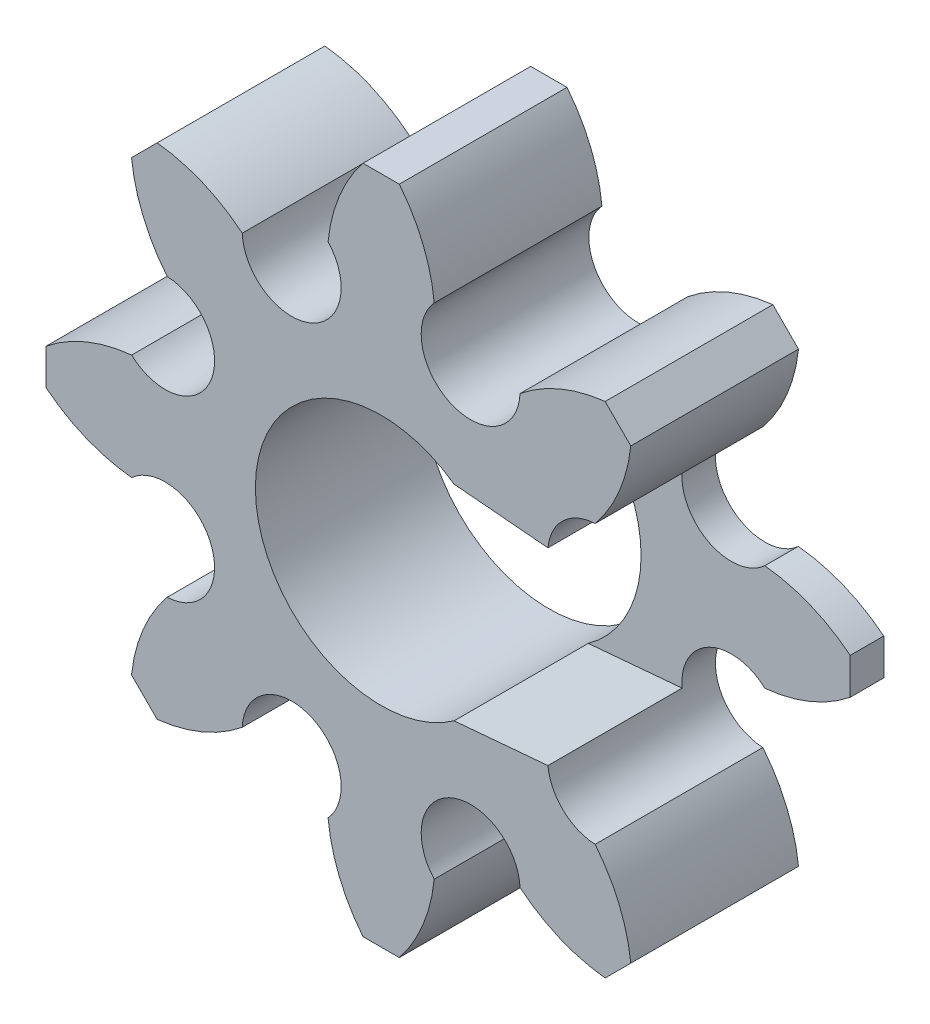
SolidWorks part; units mm, degrees
material "PLA"
ref_plane "Front Plane" through (0, 0, 0) normal (0, 0, 1) x (1, 0, 0)
ref_plane "Top Plane" through (0, 0, 0) normal (0, 1, 0) x (1, 0, 0)
ref_plane "Right Plane" through (0, 0, 0) normal (1, 0, 0) x (0, 0, -1)
other "Graphic1"
other "Graphic (Closed) -1"
sketch "Sketch1" plane through (0, 0, 0) normal (0, 0, 1) x (1, 0, 0)
  line L0 (9.559, 20.0854) -> (10.641, 20.0854)
  line L1 (16.7782, 17.5433) -> (17.5433, 16.7782)
  line L2 (20.0854, 10.641) -> (20.0854, 9.559)
  line L3 (17.5433, 3.4218) -> (16.7782, 2.6567)
  line L4 (10.641, 0.1146) -> (9.559, 0.1146)
  line L5 (3.4218, 2.6567) -> (2.6567, 3.4218)
  line L6 (0.1146, 9.559) -> (0.1146, 10.641)
  line L7 (2.6567, 16.7782) -> (3.4218, 17.5433)
  circle A0 centre (10.1, 10.1) radius 3.75
  arc A1 (11.6827, 17.5393) -> (10.641, 20.0854) centre (6.9163, 17.0752) ccw
  arc A2 (9.559, 20.0854) -> (8.5173, 17.5393) centre (13.3466, 17.0495) ccw
  arc A3 (8.5173, 17.5393) -> (5.9588, 16.4796) centre (7.4322, 16.5407) cw
  arc A4 (14.2412, 16.4796) -> (11.6827, 17.5393) centre (12.7678, 16.5407) cw
  arc A5 (16.7782, 17.5433) -> (14.2412, 16.4796) centre (17.3097, 12.7183) ccw
  arc A6 (16.4796, 14.2412) -> (17.5433, 16.7782) centre (12.781, 17.2835) ccw
  arc A7 (17.5393, 11.6827) -> (16.4796, 14.2412) centre (16.5407, 12.7678) cw
  arc A8 (20.0854, 10.641) -> (17.5393, 11.6827) centre (17.0495, 6.8534) ccw
  arc A9 (17.5393, 8.5173) -> (20.0854, 9.559) centre (17.0752, 13.2837) ccw
  arc A10 (16.4796, 5.9588) -> (17.5393, 8.5173) centre (16.5407, 7.4322) cw
  arc A11 (17.5433, 3.4218) -> (16.4796, 5.9588) centre (12.7183, 2.8903) ccw
  arc A12 (14.2412, 3.7204) -> (16.7782, 2.6567) centre (17.2835, 7.419) ccw
  arc A13 (11.6827, 2.6607) -> (14.2412, 3.7204) centre (12.7678, 3.6593) cw
  arc A14 (10.641, 0.1146) -> (11.6827, 2.6607) centre (6.8534, 3.1505) ccw
  arc A15 (8.5173, 2.6607) -> (9.559, 0.1146) centre (13.2837, 3.1248) ccw
  arc A16 (5.9588, 3.7204) -> (8.5173, 2.6607) centre (7.4322, 3.6593) cw
  arc A17 (3.4218, 2.6567) -> (5.9588, 3.7204) centre (2.8903, 7.4817) ccw
  arc A18 (3.7204, 5.9588) -> (2.6567, 3.4218) centre (7.419, 2.9165) ccw
  arc A19 (2.6607, 8.5173) -> (3.7204, 5.9588) centre (3.6593, 7.4322) cw
  arc A20 (0.1146, 9.559) -> (2.6607, 8.5173) centre (3.1505, 13.3466) ccw
  arc A21 (2.6607, 11.6827) -> (0.1146, 10.641) centre (3.1248, 6.9163) ccw
  arc A22 (3.7204, 14.2412) -> (2.6607, 11.6827) centre (3.6593, 12.7678) cw
  arc A23 (2.6567, 16.7782) -> (3.7204, 14.2412) centre (7.4817, 17.3097) ccw
  arc A24 (5.9588, 16.4796) -> (3.4218, 17.5433) centre (2.9165, 12.781) ccw
  point P79 (10.1, 10.1)
  dimension "D1" = 8
extrude "Boss-Extrude1" add sketch "Sketch1" along normal blind 5
sketch "Sketch2" plane through (0, 0, 5) normal (0, 0, 1) x (1, 0, 0)
  line L2 (12.191, 13.1627) -> (12.2742, 7.0446)
  line L3 (12.2742, 7.0446) -> (15.0742, 7.2896)
  line L4 (15.0742, 7.2896) -> (15.1128, 7.293)
  line L5 (15.1128, 7.293) -> (23.6534, 8.0401)
  line L7 (12.191, 13.1627) -> (15.0742, 12.9104)
  line L8 (15.0742, 12.9104) -> (23.6534, 12.1599)
  line L9 (23.6534, 12.1599) -> (23.6534, 8.0401)
  circle A0 centre (10.1, 10.1) radius 3.75 construction
extrude "Cut-Extrude1" cut sketch "Sketch2" against normal blind 4
